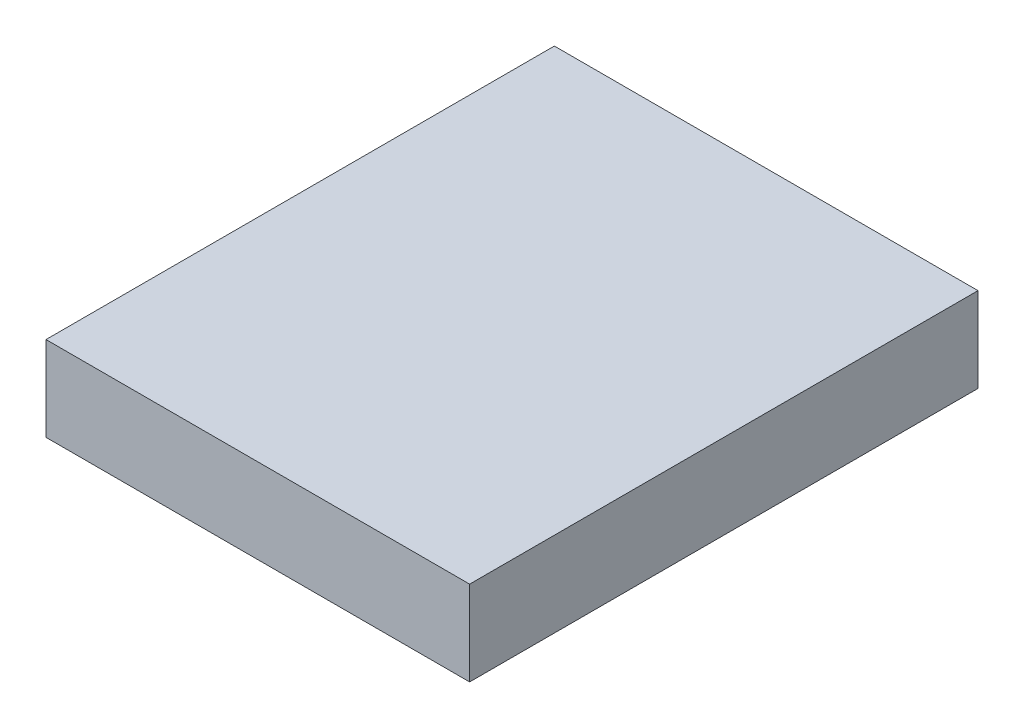
SolidWorks part; units mm, degrees
ref_plane "Alzado" through (0, 0, 0) normal (0, 0, 1) x (1, 0, 0)
ref_plane "Planta" through (0, 0, 0) normal (0, 1, 0) x (1, 0, 0)
ref_plane "Vista lateral" through (0, 0, 0) normal (1, 0, 0) x (0, 0, -1)
sketch "Croquis1" plane through (0, 0, 0) normal (0, 1, 0) x (1, 0, 0)
  line L1 (12.5, -15) -> (-12.5, -15)
  line L2 (12.5, -15) -> (12.5, 15)
  line L3 (12.5, 15) -> (-12.5, 15)
  line L4 (-12.5, -15) -> (-12.5, 15)
  line L5 (12.5, -15) -> (-12.5, 15) construction
  line L6 (12.5, 15) -> (-12.5, -15) construction
  point P0 (0, 0)
  dimension "D1" = 25
  dimension "D2" = 30
extrude "Saliente-Extruir1" add sketch "Croquis1" along normal blind 5
